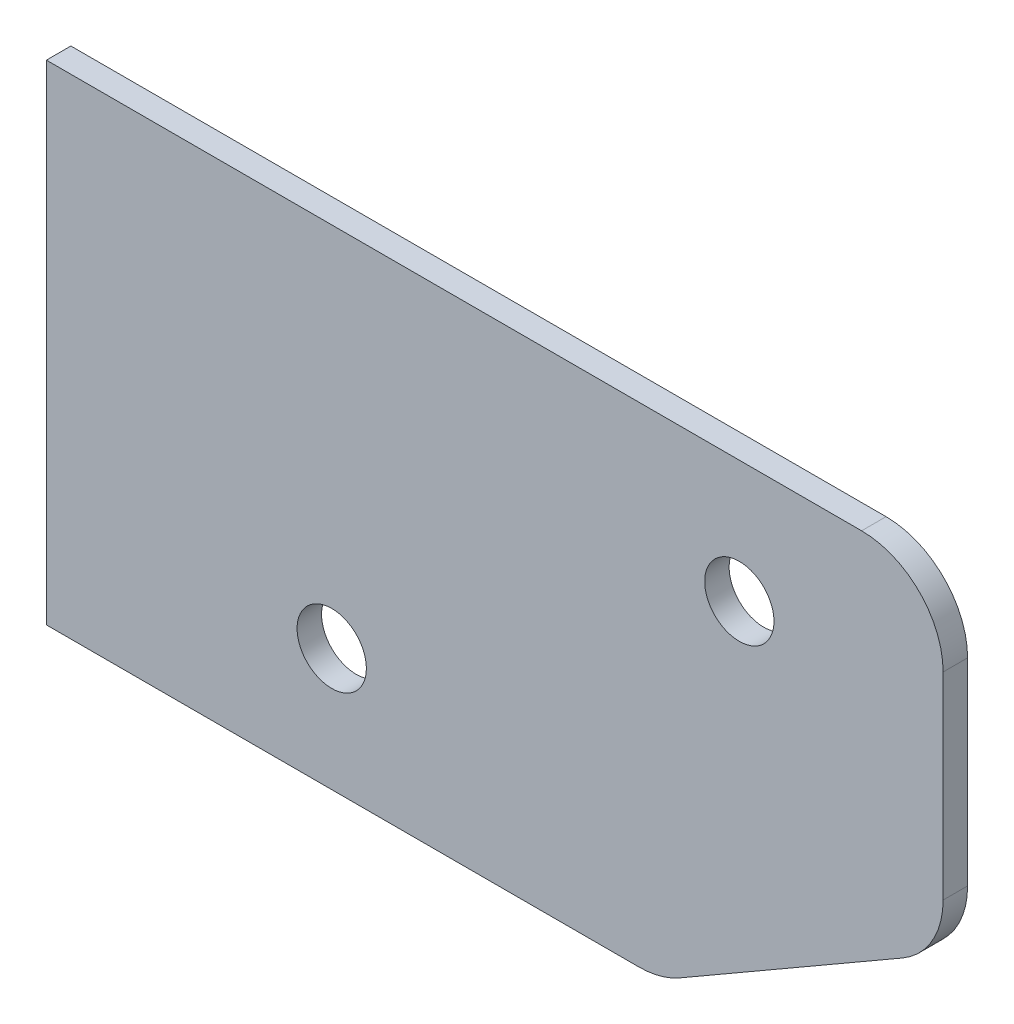
SolidWorks part; units mm, degrees
ref_plane "Front Plane" through (0, 0, 0) normal (0, 0, 1) x (1, 0, 0)
ref_plane "Top Plane" through (0, 0, 0) normal (0, 1, 0) x (1, 0, 0)
ref_plane "Right Plane" through (0, 0, 0) normal (1, 0, 0) x (0, 0, -1)
sketch "Sketch1" plane through (0, 0, 0) normal (0, 0, 1) x (1, 0, 0)
  line L0 (0, 0) -> (0, 60)
  line L1 (0, 60) -> (110, 60)
  line L2 (110, 60) -> (110, 20)
  line L3 (110, 20) -> (75.359, 0)
  line L4 (75.359, 0) -> (0, 0)
  dimension "D1" = 60
  dimension "D2" = 110
  dimension "D3" = 40
  dimension "D4" = 120
extrude "Boss-Extrude1" add sketch "Sketch1" along normal blind 3
fillet "Fillet1" radius 10 3 edges at (110, 60, 1.5) (110, 20, 1.5) (75.359, 0, 1.5)
sketch "Sketch2" plane through (0, 0, 3) normal (0, 0, 1) x (1, 0, 0)
  line L0 (100, 60) -> (0, 60) construction
  line L1 (0, 60) -> (0, 0) construction
  circle A0 centre (35, 15) radius 4.25
  circle A1 centre (85, 45) radius 4.25
  dimension "D1" = 8.5
  dimension "D2" = 45
  dimension "D4" = 15
  dimension "D5" = 50
  dimension "D3" = 35
extrude "Cut-Extrude1" cut sketch "Sketch2" against normal through all
